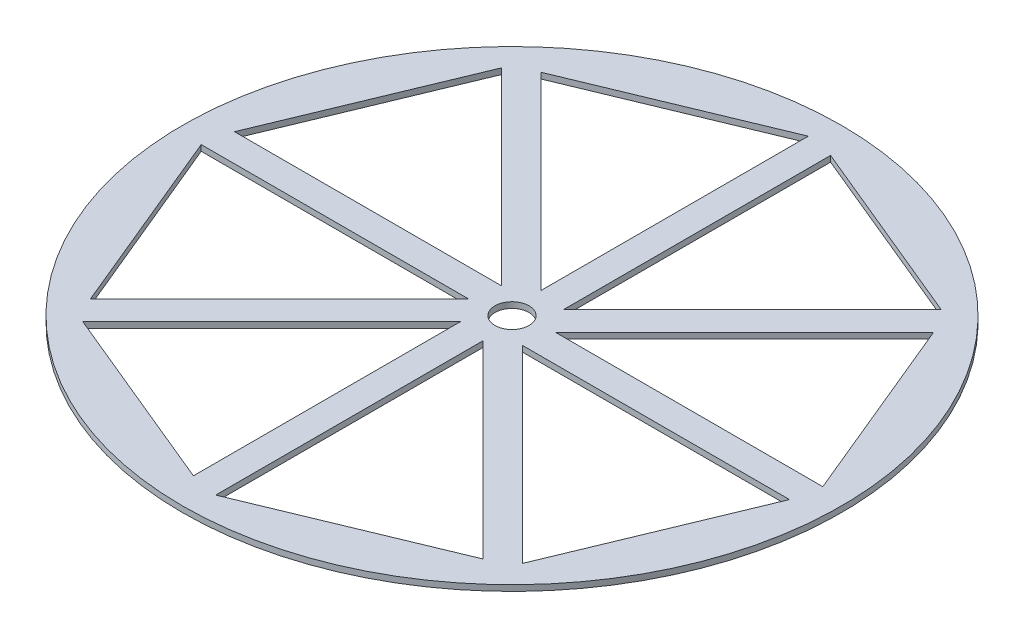
SolidWorks part; units mm, degrees
ref_plane "Front Plane" through (0, 0, 0) normal (0, 0, 1) x (1, 0, 0)
ref_plane "Top Plane" through (0, 0, 0) normal (0, 1, 0) x (1, 0, 0)
ref_plane "Right Plane" through (0, 0, 0) normal (1, 0, 0) x (0, 0, -1)
sketch "Sketch1" plane through (0, 0, 0) normal (0, 1, 0) x (1, 0, 0)
  circle A0 centre (0, 0) radius 160.3375
  circle A1 centre (0, 0) radius 8.3
  dimension "D1" = 320.675
  dimension "D2" = 16.6
extrude "Boss-Extrude1" add sketch "Sketch1" along normal blind 2.85
sketch "Sketch3" plane through (0, 2.85, 0) normal (0, 1, 0) x (1, 0, 0)
  line L0 (0, 0) -> (-160.3375, 0)
  line L1 (-145, 10) -> (-15, 10)
  line L2 (-15, 10) -> (-106.9239, 101.9239)
  line L3 (-106.9239, 101.9239) -> (-145, 10)
  line L4 (-3.5355, 147.6777) -> (-95.4594, 109.6016)
  line L5 (-95.4594, 109.6016) -> (-3.5355, 17.6777)
  line L6 (-3.5355, 17.6777) -> (-3.5355, 147.6777)
  line L7 (101.9239, 106.9239) -> (10, 145)
  line L8 (10, 145) -> (10, 15)
  line L9 (10, 15) -> (101.9239, 106.9239)
  line L10 (147.6777, 3.5355) -> (109.6016, 95.4594)
  line L11 (109.6016, 95.4594) -> (17.6777, 3.5355)
  line L12 (17.6777, 3.5355) -> (147.6777, 3.5355)
  line L13 (106.9239, -101.9239) -> (145, -10)
  line L14 (145, -10) -> (15, -10)
  line L15 (15, -10) -> (106.9239, -101.9239)
  line L16 (3.5355, -147.6777) -> (95.4594, -109.6016)
  line L17 (95.4594, -109.6016) -> (3.5355, -17.6777)
  line L18 (3.5355, -17.6777) -> (3.5355, -147.6777)
  line L19 (-101.9239, -106.9239) -> (-10, -145)
  line L20 (-10, -145) -> (-10, -15)
  line L21 (-10, -15) -> (-101.9239, -106.9239)
  line L22 (-147.6777, -3.5355) -> (-109.6016, -95.4594)
  line L23 (-109.6016, -95.4594) -> (-17.6777, -3.5355)
  line L24 (-17.6777, -3.5355) -> (-147.6777, -3.5355)
  circle A0 centre (0, 0) radius 160.3375 construction
  dimension "D1" = 130
  dimension "D2" = 130
  dimension "D3" = 45
  dimension "D4" = 10
  dimension "D5" = 15
  dimension "D6" = 8
extrude "Cut-Extrude1" cut sketch "Sketch3" against normal through all contours L2 L3 L1 | L5 L6 L4 | L8 L9 L7 | L11 L12 L10 | L14 L15 L13 | L17 L18 L16 | L20 L21 L19 | L23 L24 L22
